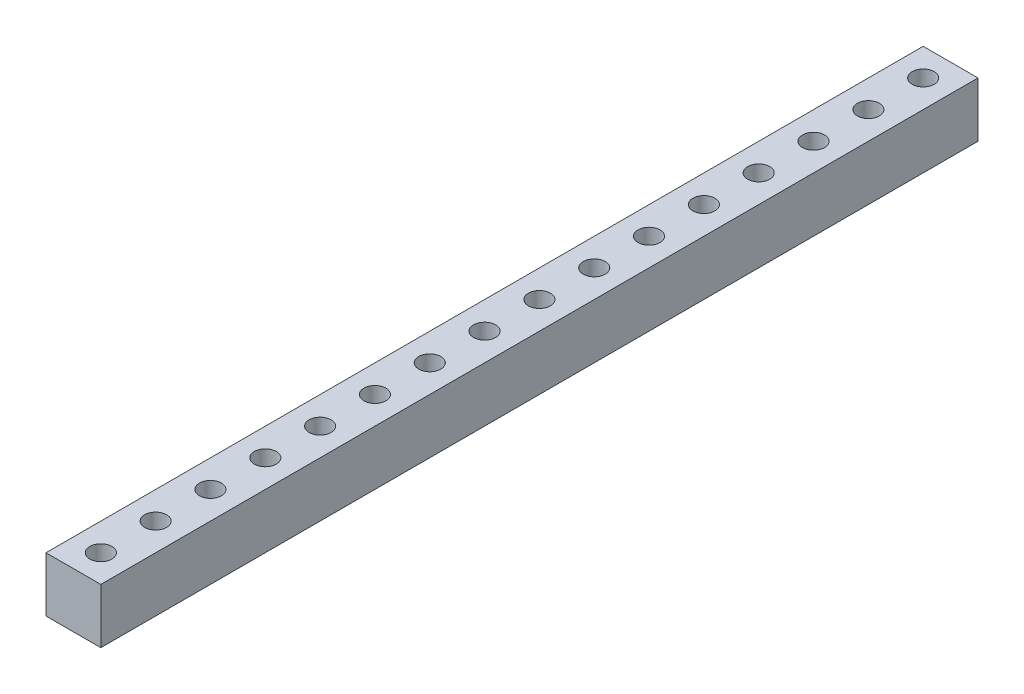
SolidWorks part; units mm, degrees
ref_plane "Front Plane" through (0, 0, 0) normal (0, 0, 1) x (1, 0, 0)
ref_plane "Top Plane" through (0, 0, 0) normal (0, 1, 0) x (1, 0, 0)
ref_plane "Right Plane" through (0, 0, 0) normal (1, 0, 0) x (0, 0, -1)
sketch "Sketch1" plane through (0, 0, 0) normal (1, 0, 0) x (0, 0, -1)
  line L1 (-20.32, -1.27) -> (20.32, -1.27)
  line L2 (-20.32, -1.27) -> (-20.32, 1.27)
  line L3 (-20.32, 1.27) -> (20.32, 1.27)
  line L4 (20.32, -1.27) -> (20.32, 1.27)
  line L5 (-20.32, -1.27) -> (20.32, 1.27) construction
  line L6 (-20.32, 1.27) -> (20.32, -1.27) construction
  point P0 (0, 0)
  dimension "D1" = 40.64
  dimension "D2" = 2.54
extrude "Boss-Extrude1" add sketch "Sketch1" along normal blind 2.54
sketch "Sketch2" plane through (0, 1.27, 0) normal (0, 1, 0) x (1, 0, 0)
  line L0 (1.27, 20.32) -> (1.27, -20.32) construction
  line L3 (2.54, 20.32) -> (0, 20.32) construction
  line L4 (2.54, -20.32) -> (0, -20.32) construction
  line L5 (1.27, -20.32) -> (1.27, -19.05)
  dimension "D1" = 1.27
hole_wizard "Ø1.0mm Dowel Hole1" positions "3DSketch1" profile "Sketch3" hole size "Ø1.0" standard "ANSI Metric" end condition through all
sketch3d "3DSketch1"
  point P0 (1.27, 1.27, 19.05)
sketch "Sketch3" plane through (1.27, 1.27, 19.05) normal (1, 0, 0) x (0, 0, 1)
  line L0 (0, 0) -> (0, 2.54)
  line L1 (0, 2.54) -> (0.51, 2.54)
  line L2 (0.51, 2.54) -> (0.51, 0)
  line L5 (0.51, 0) -> (0, 0)
  line L11 (0, -6.35) -> (0, 107.95) construction
  dimension "Thru Hole Dia." = 1.02
  dimension "Thru Hole Depth" = 2.54
pattern_linear "LPattern1" count 16 spacing 2.54 along (0, 0, -1) of "Ø1.0mm Dowel Hole1"
